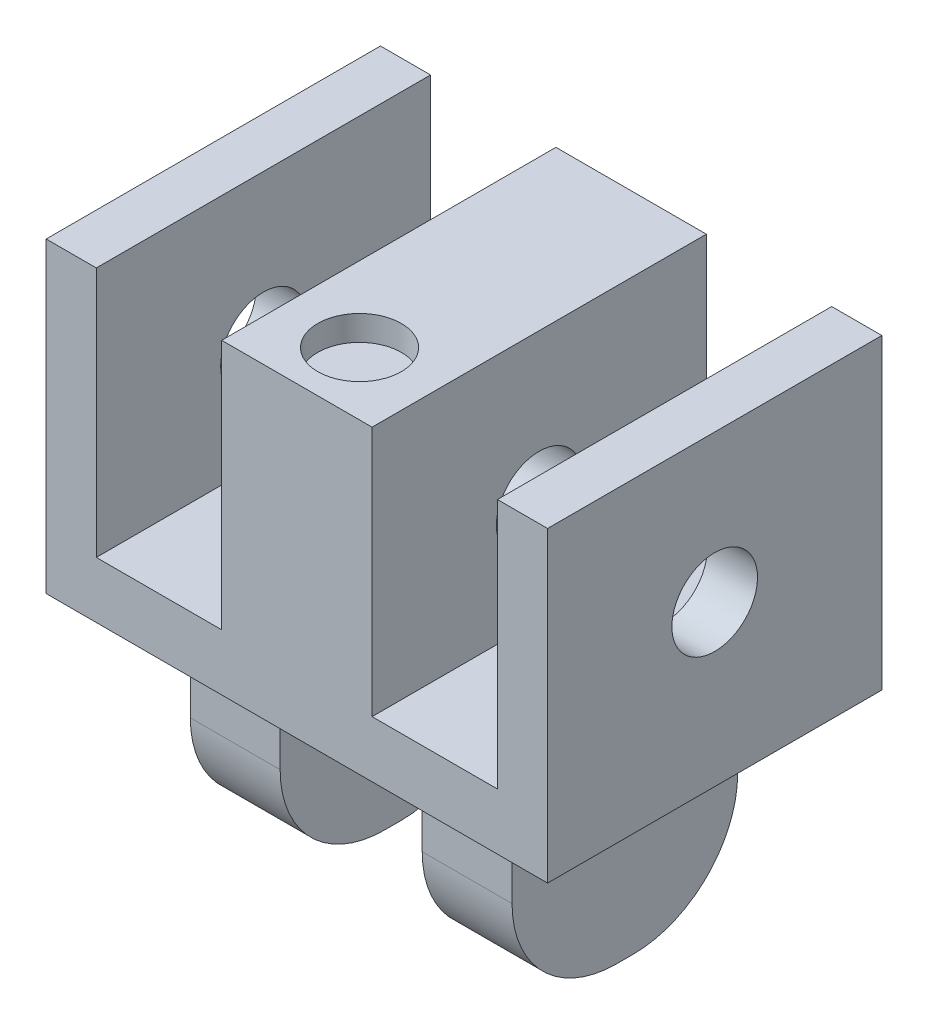
SolidWorks part; units mm, degrees
ref_plane "Front Plane" through (0, 0, 0) normal (0, 0, 1) x (1, 0, 0)
ref_plane "Top Plane" through (0, 0, 0) normal (0, 1, 0) x (1, 0, 0)
ref_plane "Right Plane" through (0, 0, 0) normal (1, 0, 0) x (0, 0, -1)
sketch "Sketch1" plane through (0, 0, 0) normal (0, 0, 1) x (1, 0, 0)
  line L1 (-60, 60) -> (60, 60)
  line L2 (-60, 60) -> (-60, -60)
  line L3 (-60, -60) -> (60, -60)
  line L4 (60, 60) -> (60, -60)
  line L5 (-60, 60) -> (60, -60) construction
  line L6 (-60, -60) -> (60, 60) construction
  line L7 (17, -60) -> (-17, -60)
  line L8 (17, -60) -> (17, -13.5)
  line L9 (17, -13.5) -> (-17, -13.5)
  line L10 (-17, -60) -> (-17, -13.5)
  point P0 (0, 0)
  dimension "D1" = 120
  dimension "D2" = 120
  dimension "D3" = 46.5
  dimension "D4" = 34
  dimension "D5" = 43
extrude "Boss-Extrude1" add sketch "Sketch1" along normal blind 54 contours L3 L10 L9 L8 L4 L1 L2
sketch "Sketch2" plane through (60, 0, 0) normal (1, 0, 0) x (0, 0, -1)
  line L0 (-54, -13.5) -> (0, -13.5) construction
  circle A0 centre (-27, -24.75) radius 10.25
  dimension "D1" = 11.25
extrude "Cut-Extrude1" cut sketch "Sketch2" against normal through all both and the other way through all
sketch "Sketch3" plane through (60, 0, 0) normal (1, 0, 0) x (0, 0, -1)
  line L0 (-54, 60) -> (0, 60) construction
  circle A0 centre (-27, 24.75) radius 10.25
  dimension "D1" = 35.25
extrude "Cut-Extrude2" cut sketch "Sketch3" against normal through all both and the other way through all
sketch "Sketch4" plane through (0, 0, 54) normal (0, 0, 1) x (1, 0, 0)
  line L1 (-60, -60) -> (-38.5, -60)
  line L2 (-60, -60) -> (-60, -13.5)
  line L3 (-60, -13.5) -> (-38.5, -13.5)
  line L4 (-38.5, -60) -> (-38.5, -13.5)
  line L5 (60, -60) -> (38.5, -60)
  line L6 (60, -60) -> (60, -13.5)
  line L7 (60, -13.5) -> (38.5, -13.5)
  line L8 (38.5, -60) -> (38.5, -13.5)
  dimension "D1" = 46.5
  dimension "D2" = 46.5
extrude "Cut-Extrude3" cut sketch "Sketch4" against normal through all both and the other way through all
fillet "Fillet1" radius 25 4 edges at (-27.75, -60, 54) (-27.75, -60, 0) (27.75, -60, 0) (27.75, -60, 54)
sketch "Sketch5" plane through (0, 60, 0) normal (0, 1, 0) x (1, 0, 0)
  line L1 (60, 0) -> (-60, 0)
  line L2 (60, 0) -> (60, 13)
  line L3 (60, 13) -> (-60, 13)
  line L4 (-60, 0) -> (-60, 13)
  line L5 (-60, -54) -> (60, -54)
  line L6 (-60, -54) -> (-60, -67)
  line L7 (-60, -67) -> (60, -67)
  line L8 (60, -54) -> (60, -67)
  dimension "D1" = 13
  dimension "D2" = 13
extrude "Boss-Extrude2" add sketch "Sketch5" against normal blind 73.5
sketch "Sketch6" plane through (0, 60, 0) normal (0, 1, 0) x (1, 0, 0)
  line L0 (60, 13) -> (-60, 13) construction
  line L1 (-48, 13) -> (-18, 13)
  line L2 (-48, 13) -> (-48, -67)
  line L3 (-48, -67) -> (-18, -67)
  line L4 (-18, 13) -> (-18, -67)
  line L5 (-60, -67) -> (60, -67) construction
  line L6 (-60, -67) -> (-60, 13) construction
  line L11 (0, 0) -> (0, 35.5501) construction
  line L12 (18, 13) -> (18, -67)
  line L13 (48, -67) -> (18, -67)
  line L14 (48, 13) -> (48, -67)
  line L15 (48, 13) -> (18, 13)
  dimension "D1" = 12
  dimension "D2" = 30
extrude "Cut-Extrude4" cut sketch "Sketch6" against normal blind 60
sketch "Sketch7" plane through (0, 60, 0) normal (0, 1, 0) x (1, 0, 0)
  line L0 (-18, -67) -> (18, -67) construction
  circle A0 centre (0, -52) radius 10
  dimension "D1" = 15
extrude "Cut-Extrude5" cut sketch "Sketch7" against normal blind 6
